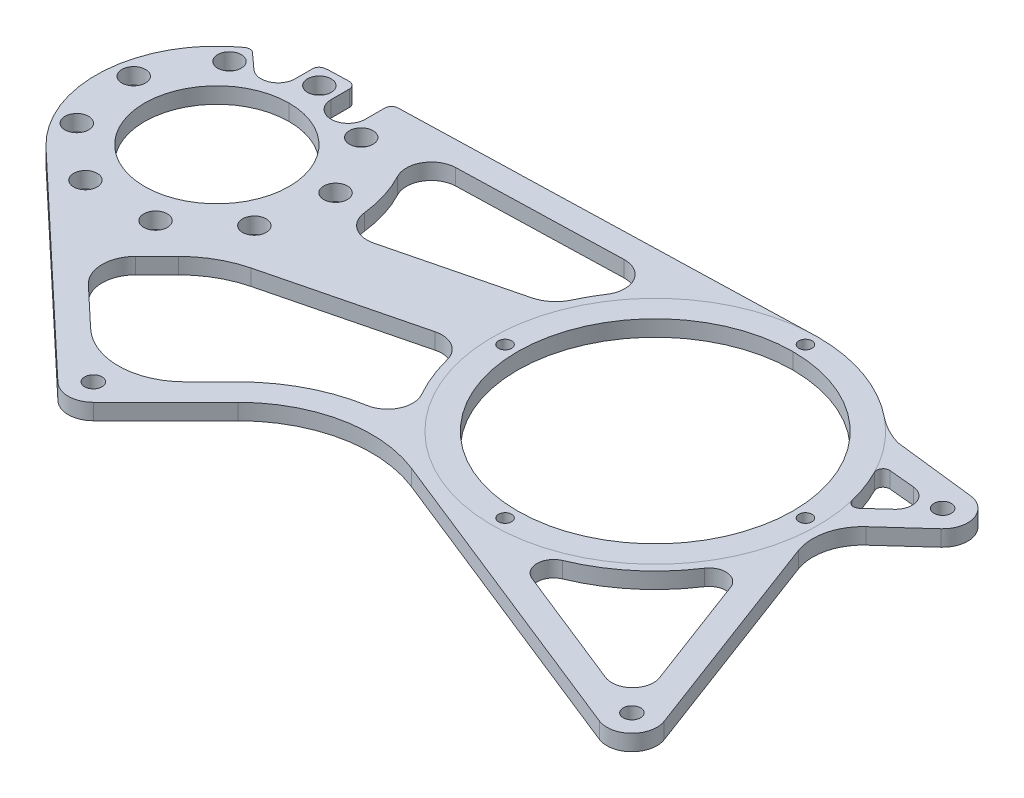
SolidWorks part; units mm, degrees
material "6061-T6 (SS)"
ref_plane "X-Y Datum" through (0, 0, 0) normal (0, 0, 1) x (1, 0, 0)
ref_plane "X-Z Datum" through (0, 0, 0) normal (0, 1, 0) x (1, 0, 0)
ref_plane "Y-Z Datum" through (0, 0, 0) normal (1, 0, 0) x (0, 0, -1)
sketch "Master Sketch " plane through (0, 0, 0) normal (0, 1, 0) x (1, 0, 0)
  line L0 (0, 0) -> (116.84, 0) construction
  line L1 (0, 0) -> (-54.61, 0) construction
  line L2 (116.84, 0) -> (228.6, 0) construction
  line L3 (228.6, 0) -> (228.6, 146.8882) construction
  line L4 (123.19, 0) -> (123.19, 116.0018) construction
  line L5 (-54.61, 0) -> (-414.02, 0) construction
  line L6 (-54.61, 0) -> (-54.61, 127) construction
  line L7 (123.19, 168.4528) -> (123.19, 177.9778) construction
  line L8 (228.6, 146.8882) -> (123.19, 116.0018) construction
  line L9 (123.19, 116.0018) -> (228.6, 0) construction
  line L10 (0, 0) -> (123.19, 116.0018) construction
  line L11 (0, 0) -> (-54.61, 127) construction
  line L12 (-54.61, 127) -> (123.19, 116.0018) construction
  line L13 (228.6, 146.8882) -> (-54.61, 127) construction
  line L14 (0, 0) -> (0, 123.622) construction
  line L15 (-86.1521, 93.553) -> (-6.535, 18.4704)
  line L16 (-54.61, 172.974) -> (123.19, 177.9778)
  line L17 (194.7449, 124.6975) -> (209.653, 138.231)
  line L19 (189.7169, 103.8914) -> (220.4344, 22.1488)
  line L20 (6.7352, 18.6648) -> (34.256, 46.1856)
  line L21 (207.987, 9.9519) -> (89.0101, 57.4446)
  line L22 (204.3537, 154.7444) -> (173.1, 158.388)
  circle A0 centre (0, 0) radius 12.7 construction
  circle A1 centre (228.6, 146.8882) radius 12.7 construction
  circle A2 centre (228.6, 0) radius 12.7 construction
  circle A3 centre (-414.02, 0) radius 12.7 construction
  circle A4 centre (123.19, 116.0018) radius 52.451
  circle A5 centre (123.19, 116.0018) radius 57.15 construction
  circle A6 centre (123.19, 116.0018) radius 61.976 construction
  circle A7 centre (-54.61, 127) radius 45.974
  circle A8 centre (-54.61, 127) radius 39 construction
  circle A9 centre (203.2507, 145.2835) radius 3 construction
  circle A10 centre (211.5182, 18.7982) radius 3 construction
  circle A11 centre (0, 25.4) radius 3 construction
  circle A12 centre (0, 25.4) radius 9.525
  circle A13 centre (211.5182, 18.7982) radius 9.525
  circle A14 centre (203.2507, 145.2835) radius 9.525
  arc A17 (56.2619, 120.1418) -> (168.2859, 66.3745) centre (123.19, 116.0018) ccw construction
  arc A18 (123.19, 177.9778) -> (162.2274, 164.1382) centre (123.19, 116.0018) cw
  circle A19 centre (123.19, 116.0018) radius 67.056 construction
  arc A20 (194.7449, 124.6975) -> (189.7169, 103.8914) centre (207.5493, 110.5926) ccw
  arc A21 (173.1, 158.388) -> (162.2274, 164.1382) centre (182.226, 188.7982) cw
  arc A22 (89.0101, 57.4446) -> (34.256, 46.1856) centre (70.177, 10.2646) ccw
  circle A23 centre (-54.61, 127) radius 25.908 construction
  circle A24 centre (-54.61, 127) radius 27.4955
  circle A25 centre (123.19, 173.1518) radius 2.5 construction
  circle A26 centre (-41.2712, 163.648) radius 6.5
  circle A27 centre (-67.9488, 163.648) radius 6.5
  point P9 (123.19, 0)
  point P23 (-54.61, 166)
  point P27 (-41.2712, 163.648)
  point P28 (-29.5413, 156.8757)
  point P29 (-20.835, 146.5)
  point P30 (-16.2025, 133.7723)
  point P31 (-16.2025, 120.2277)
  point P32 (-20.835, 107.5)
  point P33 (-29.5413, 97.1243)
  point P34 (-41.2712, 90.352)
  point P35 (-54.61, 88)
  point P36 (-67.9488, 90.352)
  point P37 (-79.6787, 97.1243)
  point P38 (-88.385, 107.5)
  point P39 (-93.0175, 120.2277)
  point P40 (-93.0175, 133.7723)
  point P41 (-88.385, 146.5)
  point P42 (-79.6787, 156.8757)
  point P43 (-67.9488, 163.648)
  point P44 (-54.61, 127)
  point P66 (190.246, 116.0018)
  point P74 (185.166, 116.0018)
  point P75 (0, 0)
  point P77 (163.0683, 163.4438)
  point P80 (74.3713, 70.0317)
  point P87 (0, 0)
  point P88 (0, 0)
  dimension "D1" = 105.41
  dimension "D2" = 25.4
  dimension "D8" = 116.0018
  dimension "D11" = 104.902
  dimension "D12" = 114.3
  dimension "D13" = 123.952
  dimension "D14" = 91.948
  dimension "D15" = 78
  dimension "D17" = 6
  dimension "D21" = 19.05
  dimension "D23" = 13
  dimension "D25" = 19.05
  dimension "D26" = 31.75
  dimension "D27" = 50.8
  dimension "D28" = 1.5875
  dimension "D30" = 51.816
  dimension "D31" = 5
  dimension "D32" = 25.4
  dimension "D3" = 146.8882
  dimension "D4" = 171.45
  dimension "D5" = 111.76
  dimension "D6" = 116.84
  dimension "D7" = 54.61
  dimension "D9" = 642.62
  dimension "D10" = 127
  dimension "D18" = 25.4
  dimension "D19" = 25.4
  dimension "D20" = 5.588
  dimension "D22" = 228.6
  dimension "D29" = 45
  dimension "D33" = 42.1263
  dimension "D34" = 13.1045
  dimension "D24" = 5.08
  dimension "D16" = 18
extrude "Boss-Extrude2" add sketch "Master Sketch " along normal mid plane 6.096
hole_wizard "Ø5.0mm Dowel Hole1" positions "Sketch26" profile "Sketch27" hole size "Ø5.0" standard "ANSI Metric" end condition through all
sketch "Sketch26" plane through (0, 3.048, 0) normal (0, 1, 0) x (1, 0, 0)
  point P5 (123.19, 173.1518)
sketch "Sketch27" plane through (123.19, 3.048, -173.1518) normal (1, 0, 0) x (0, 0, 1)
  line L0 (0, 0) -> (0, 6.096)
  line L1 (0, 6.096) -> (2.5, 6.096)
  line L2 (2.5, 6.096) -> (2.5, 0)
  line L5 (2.5, 0) -> (0, 0)
  line L11 (0, -6.35) -> (0, 107.95) construction
  dimension "Thru Hole Dia." = 5
  dimension "Thru Hole Depth" = 6.096
pattern_circular "CirPattern4" count 4 over 360 about axis through (123.19, 0, -116.0018) along (0, 1, 0) of "Ø5.0mm Dowel Hole1"
hole_wizard "M6 Clearance Hole4" positions "Sketch20" profile "Sketch21" hole size "M6" standard "ANSI Metric" end condition through all
sketch "Sketch20" plane through (0, 3.048, 0) normal (0, 1, 0) x (1, 0, 0)
  point P0 (203.2507, 145.2835)
  point P3 (211.5182, 18.7982)
  point P6 (0, 25.4)
  point P9 (203.2507, 145.2835)
sketch "Sketch21" plane through (203.2507, 3.048, -145.2835) normal (1, 0, 0) x (0, 0, 1)
  line L0 (0, 0) -> (0, 6.096)
  line L1 (0, 6.096) -> (3.3, 6.096)
  line L2 (3.3, 6.096) -> (3.3, 0)
  line L5 (3.3, 0) -> (0, 0)
  line L11 (0, -6.35) -> (0, 107.95) construction
  dimension "Thru Hole Dia." = 6.6
  dimension "Thru Hole Depth" = 6.096
hole_wizard "M8 Clearance Hole1" positions "Sketch24" profile "Sketch25" hole size "M8" standard "ANSI Metric" end condition through all
sketch "Sketch24" plane through (0, 3.048, 0) normal (0, 1, 0) x (1, 0, 0)
  point P2 (-54.61, 166)
sketch "Sketch25" plane through (-54.61, 3.048, -166) normal (1, 0, 0) x (0, 0, 1)
  line L0 (0, 0) -> (0, 6.096)
  line L1 (0, 6.096) -> (4.5, 6.096)
  line L2 (4.5, 6.096) -> (4.5, 0)
  line L5 (4.5, 0) -> (0, 0)
  line L11 (0, -6.35) -> (0, 107.95) construction
  dimension "Thru Hole Dia." = 9
  dimension "Thru Hole Depth" = 6.096
pattern_circular "CirPattern3" count 9 over 360 about axis through (-54.61, 0, -127) along (0, 1, 0) of "M8 Clearance Hole1"
ref_plane "Plane2" through (-54.61, 0, 0) normal (1, 0, 0) x (0, 0, -1)
ref_plane "Plane1" through (123.19, 0, 0) normal (1, 0, 0) x (0, 0, -1)
split line "Split Line2"
split line "Split Line3"
ref_point "Point2"
ref_point "Point3"
sketch "Sketch28" plane through (0, 3.048, 0) normal (0, 1, 0) x (1, 0, 0)
  circle A0 centre (123.19, 116.0018) radius 61.976 construction
  circle A1 centre (123.19, 116.0018) radius 61.976
split line "Split Line4"
sketch "Topology 1" plane through (0, 3.048, 0) normal (0, 1, 0) x (1, 0, 0)
  line L0 (145.3498, 45.211) -> (198.1607, 24.1302)
  line L1 (206.4589, 32.2614) -> (188.0555, 81.2349)
  line L2 (195.7351, 153.1787) -> (183.0397, 153.6291)
  line L3 (92.5413, 66.2908) -> (211.5182, 18.7982) construction
  line L4 (211.5182, 18.7982) -> (180.8006, 100.5409) construction
  line L5 (191.1278, 134.2783) -> (199.7781, 142.1311)
  line L6 (188.3427, 131.75) -> (203.2507, 145.2835) construction
  line L7 (204.3537, 154.7444) -> (173.1, 158.388)
  line L8 (6.7352, 18.6648) -> (34.256, 46.1856) construction
  line L9 (119.7044, 177.8797) -> (123.19, 177.9778) construction
  line L10 (119.7044, 177.8797) -> (123.19, 177.9778)
  line L11 (6.7352, 18.6648) -> (34.256, 46.1856)
  line L12 (11.5992, 36.9992) -> (27.5208, 52.9208)
  line L14 (-17.1171, 47.0221) -> (-17.1171, 64.5798)
  line L15 (-6.2723, 77.1436) -> (59.6042, 86.8711)
  line L16 (119.7044, 177.8797) -> (-54.61, 172.974)
  line L17 (-86.1521, 93.553) -> (-6.535, 18.4704)
  line L18 (6.7352, 18.6648) -> (34.256, 46.1856)
  line L19 (89.0101, 57.4446) -> (207.987, 9.9519)
  line L20 (220.4344, 22.1488) -> (189.7169, 103.8914)
  line L21 (194.7449, 124.6975) -> (209.653, 138.231)
  line L22 (204.3537, 154.7444) -> (173.1, 158.388)
  line L23 (119.7044, 177.8797) -> (-54.61, 172.974)
  line L24 (-86.1521, 93.553) -> (-6.535, 18.4704)
  line L26 (89.0101, 57.4446) -> (207.987, 9.9519)
  line L27 (220.4344, 22.1488) -> (189.7169, 103.8914)
  line L28 (194.7449, 124.6975) -> (209.653, 138.231)
  line L30 (73.4651, 167.0496) -> (-14.7002, 164.5684)
  line L31 (-4.4748, 145.7986) -> (62.0635, 147.6712)
  line L32 (-13.1304, 37.7826) -> (-11.934, 36.6543)
  line L33 (119.9724, 168.3585) -> (-54.342, 163.4528) construction
  line L34 (0, 25.4) -> (27.5208, 52.9208) construction
  arc A0 (162.2274, 164.1382) -> (123.19, 177.9778) centre (123.19, 116.0018) ccw construction
  arc A1 (162.2274, 164.1382) -> (123.19, 177.9778) centre (123.19, 116.0018) ccw
  arc A2 (145.5002, 54.1144) -> (179.5195, 82.0197) centre (123.19, 116.0018) ccw
  arc A3 (179.5195, 82.0197) -> (188.0555, 81.2349) centre (183.5974, 79.5596) cw
  arc A4 (119.4901, 181.6837) -> (164.6272, 167.0974) centre (123.19, 116.0018) ccw construction
  arc A5 (145.5002, 54.1144) -> (145.3498, 45.211) centre (147.1154, 49.6341) ccw
  arc A6 (206.4589, 32.2614) -> (198.1607, 24.1302) centre (200.5148, 30.0277) cw
  arc A7 (172.1385, 154.0158) -> (184.0265, 127.8317) centre (123.19, 116.0018) cw
  arc A8 (162.2274, 164.1382) -> (173.1, 158.388) centre (182.226, 188.7982) ccw
  arc A9 (119.7044, 177.8797) -> (162.2274, 164.1382) centre (123.19, 116.0018) ccw
  arc A10 (-54.61, 172.974) -> (-86.1521, 93.553) centre (-54.61, 127) ccw
  arc A11 (-6.535, 18.4704) -> (6.7352, 18.6648) centre (0, 25.4) ccw
  arc A12 (89.0101, 57.4446) -> (34.256, 46.1856) centre (70.177, 10.2646) ccw
  arc A13 (207.987, 9.9519) -> (220.4344, 22.1488) centre (211.5182, 18.7982) ccw
  arc A14 (194.7449, 124.6975) -> (189.7169, 103.8914) centre (207.5493, 110.5926) ccw
  arc A15 (209.653, 138.231) -> (204.3537, 154.7444) centre (203.2507, 145.2835) ccw
  arc A16 (162.2274, 164.1382) -> (173.1, 158.388) centre (182.226, 188.7982) ccw
  arc A17 (119.7044, 177.8797) -> (162.2274, 164.1382) centre (123.19, 116.0018) ccw
  arc A18 (-54.61, 172.974) -> (-86.1521, 93.553) centre (-54.61, 127) ccw
  arc A19 (-6.535, 18.4704) -> (6.7352, 18.6648) centre (0, 25.4) ccw
  arc A21 (207.987, 9.9519) -> (220.4344, 22.1488) centre (211.5182, 18.7982) ccw
  arc A22 (194.7449, 124.6975) -> (189.7169, 103.8914) centre (207.5493, 110.5926) ccw
  arc A23 (209.653, 138.231) -> (204.3537, 154.7444) centre (203.2507, 145.2835) ccw
  arc A24 (180.1768, 148.8698) -> (185.9641, 135.6794) centre (123.19, 116.0018) cw
  arc A25 (175.1477, 156.3527) -> (187.7664, 128.559) centre (123.19, 116.0018) cw construction
  arc A26 (191.1278, 134.2783) -> (185.9641, 135.6794) centre (188.9937, 136.6291) cw
  arc A27 (183.0397, 153.6291) -> (180.1768, 148.8698) centre (182.9271, 150.4561) ccw
  arc A28 (199.7781, 142.1311) -> (195.7351, 153.1787) centre (195.51, 146.8327) ccw
  arc A29 (89.0101, 57.4446) -> (34.256, 46.1856) centre (70.177, 10.2646) ccw construction
  arc A30 (89.0101, 57.4446) -> (34.256, 46.1856) centre (70.177, 10.2646) ccw
  arc A31 (63.8869, 70.2607) -> (27.5208, 52.9208) centre (70.177, 10.2646) ccw
  arc A32 (7.5766, 36.6135) -> (-7.9019, 36.3867) centre (0, 25.4) ccw
  arc A33 (67.8443, 88.1113) -> (82.4046, 69.3373) centre (123.19, 116.0018) ccw
  arc A34 (65.8116, 83.8223) -> (68.3344, 79.6884) centre (123.19, 116.0018) ccw
  arc A35 (64.4419, 86.3967) -> (79.8973, 66.4686) centre (123.19, 116.0018) ccw construction
  arc A36 (-10.3254, 149.2911) -> (-17.0182, 159.3246) centre (-54.61, 127) ccw
  arc A37 (70.0507, 147.896) -> (88.6754, 167.4777) centre (123.19, 116.0018) cw
  arc A38 (67.2815, 150.6721) -> (75.8397, 161.6717) centre (123.19, 116.0018) cw
  arc A39 (66.7839, 149.8567) -> (86.5536, 170.6422) centre (123.19, 116.0018) cw construction
  arc A40 (-17.0182, 159.3246) -> (-14.7002, 164.5684) centre (-14.6109, 161.3947) cw
  arc A41 (92.5413, 66.2908) -> (27.5208, 52.9208) centre (70.177, 10.2646) ccw construction
  arc A42 (-10.3254, 149.2911) -> (-4.4748, 145.7986) centre (-4.6534, 152.1461) ccw
  arc A43 (67.2815, 150.6721) -> (62.0635, 147.6712) centre (61.8849, 154.0187) cw
  arc A44 (75.8397, 161.6717) -> (73.4651, 167.0496) centre (73.5544, 163.8759) ccw
  arc A45 (-6.2723, 77.1436) -> (-17.1171, 64.5798) centre (-4.4171, 64.5798) ccw
  arc A46 (-17.1171, 47.0221) -> (-13.1304, 37.7826) centre (-4.4171, 47.0221) ccw
  arc A47 (7.5766, 36.6135) -> (11.5992, 36.9992) centre (9.3541, 39.2442) ccw
  arc A48 (-7.9019, 36.3867) -> (-11.934, 36.6543) centre (-9.7557, 38.9642) cw
  arc A49 (65.8116, 83.8223) -> (59.6042, 86.8711) centre (60.4947, 80.8405) ccw
  arc A50 (68.3344, 79.6884) -> (63.8869, 70.2607) centre (63.2512, 76.3235) cw
  point P69 (-79.6171, 100.4826)
  point P105 (-17.1171, 75.5422)
  point P108 (-17.1171, 41.5422)
  dimension "D4" = 4.7625
  dimension "D5" = 6.35
  dimension "D8" = 3.175
  dimension "D9" = 6.35
  dimension "D11" = 3.175
  dimension "D17" = 6.35
  dimension "D18" = 6.35
  dimension "D19" = 3.175
  dimension "D20" = 12.7
  dimension "D21" = 12.7
  dimension "D22" = 3.175
  dimension "D23" = 6.096
  dimension "D24" = 49.5784
  dimension "D25" = 13.5331
  dimension "D14" = 19.05
  dimension "D15" = 34
  dimension "D1" = 0
  dimension "D2" = 9.525
  dimension "D3" = 3.81
  dimension "D6" = 9.525
  dimension "D7" = 3.81
  dimension "D10" = 9.525
  dimension "D12" = 3.81
  dimension "D13" = 9.525
  dimension "D16" = 3.81
sketch "Topology 3" plane through (0, 3.048, 0) normal (0, 1, 0) x (1, 0, 0)
  line L0 (148.2326, 44.0603) -> (194.8213, 25.4632)
  line L1 (205.1941, 35.6272) -> (188.9001, 78.9873)
  line L2 (190.6747, 146.7902) -> (180.8059, 147.7126)
  line L3 (187.4193, 129.4727) -> (194.3519, 135.7661)
  line L4 (189.0588, 130.9611) -> (203.9669, 144.4946) construction
  line L5 (17.4418, 42.8418) -> (27.5208, 52.9208)
  line L6 (-33.0328, 56.5514) -> (-17.9453, 42.3233)
  line L7 (119.7044, 177.8797) -> (-54.61, 172.974)
  line L8 (-86.1521, 93.553) -> (-6.535, 18.4704)
  line L9 (6.7352, 18.6648) -> (34.256, 46.1856)
  line L10 (89.0101, 57.4446) -> (207.987, 9.9519)
  line L11 (220.4344, 22.1488) -> (189.7169, 103.8914)
  line L12 (194.7449, 124.6975) -> (209.653, 138.231)
  line L13 (204.3537, 154.7444) -> (173.1, 158.388)
  line L14 (119.7044, 177.8797) -> (-54.61, 172.974)
  line L15 (-86.1521, 93.553) -> (-6.535, 18.4704)
  line L16 (6.7352, 18.6648) -> (34.256, 46.1856)
  line L17 (89.0101, 57.4446) -> (207.987, 9.9519)
  line L18 (220.4344, 22.1488) -> (189.7169, 103.8914)
  line L19 (194.7449, 124.6975) -> (209.653, 138.231)
  line L22 (-7.4578, 92.9346) -> (48.4864, 106.9206)
  line L23 (60.6168, 166.688) -> (-1.6638, 164.9353)
  line L24 (7.6514, 124.4645) -> (55.6594, 136.4665)
  line L25 (-33.2997, 74.7712) -> (-25.158, 82.9129)
  line L26 (119.9724, 168.3585) -> (-54.342, 163.4528) construction
  line L27 (-79.6171, 100.4826) -> (0, 25.4) construction
  line L28 (0, 25.4) -> (27.5208, 52.9208) construction
  line L29 (92.5413, 66.2908) -> (211.5182, 18.7982) construction
  line L30 (211.5182, 18.7982) -> (180.8006, 100.5409) construction
  line L32 (204.3537, 154.7444) -> (173.1, 158.388)
  line L33 (203.2507, 145.2835) -> (123.19, 116.0018) construction
  arc A0 (123.19, 54.0258) -> (182.1581, 96.9285) centre (123.19, 116.0018) ccw
  arc A1 (148.1536, 55.8231) -> (177.6482, 80.2392) centre (123.19, 116.0018) ccw
  arc A3 (178.398, 144.1638) -> (183.3968, 130.7042) centre (123.19, 116.0018) cw
  arc A4 (59.8962, 69.7071) -> (27.5208, 52.9208) centre (70.177, 10.2646) ccw
  arc A7 (61.4889, 110.1712) -> (82.4046, 69.3373) centre (123.19, 116.0018) ccw
  arc A8 (162.2274, 164.1382) -> (173.1, 158.388) centre (182.226, 188.7982) ccw
  arc A9 (119.7044, 177.8797) -> (162.2274, 164.1382) centre (123.19, 116.0018) ccw
  arc A10 (-54.61, 172.974) -> (-86.1521, 93.553) centre (-54.61, 127) ccw
  arc A11 (-6.535, 18.4704) -> (6.7352, 18.6648) centre (0, 25.4) ccw
  arc A12 (89.0101, 57.4446) -> (34.256, 46.1856) centre (70.177, 10.2646) ccw
  arc A13 (207.987, 9.9519) -> (220.4344, 22.1488) centre (211.5182, 18.7982) ccw
  arc A14 (194.7449, 124.6975) -> (189.7169, 103.8914) centre (207.5493, 110.5926) ccw
  arc A15 (209.653, 138.231) -> (204.3537, 154.7444) centre (203.2507, 145.2835) ccw
  arc A16 (162.2274, 164.1382) -> (173.1, 158.388) centre (182.226, 188.7982) ccw
  arc A17 (119.7044, 177.8797) -> (162.2274, 164.1382) centre (123.19, 116.0018) ccw
  arc A18 (-54.61, 172.974) -> (-86.1521, 93.553) centre (-54.61, 127) ccw
  arc A19 (-6.535, 18.4704) -> (6.7352, 18.6648) centre (0, 25.4) ccw
  arc A20 (89.0101, 57.4446) -> (34.256, 46.1856) centre (70.177, 10.2646) ccw
  arc A21 (207.987, 9.9519) -> (220.4344, 22.1488) centre (211.5182, 18.7982) ccw
  arc A22 (194.7449, 124.6975) -> (189.7169, 103.8914) centre (207.5493, 110.5926) ccw
  arc A23 (209.653, 138.231) -> (204.3537, 154.7444) centre (203.2507, 145.2835) ccw
  arc A24 (60.0304, 100.017) -> (66.5532, 83.8005) centre (123.19, 116.0018) ccw
  arc A25 (63.439, 132.459) -> (88.6754, 167.4777) centre (123.19, 116.0018) cw
  arc A26 (64.0981, 143.4389) -> (68.8318, 151.9162) centre (123.19, 116.0018) cw
  arc A27 (-4.1248, 132.6464) -> (-9.7981, 150.9276) centre (-54.61, 127) ccw
  arc A28 (92.5413, 66.2908) -> (27.5208, 52.9208) centre (70.177, 10.2646) ccw construction
  arc A29 (58.328, 109.8725) -> (80.3152, 66.9467) centre (123.19, 116.0018) ccw construction
  arc A30 (60.378, 133.3021) -> (86.9072, 170.1148) centre (123.19, 116.0018) cw construction
  arc A31 (123.19, 50.8508) -> (185.179, 95.9514) centre (123.19, 116.0018) ccw construction
  arc A33 (205.1941, 35.6272) -> (194.8213, 25.4632) centre (197.7639, 32.8351) cw
  arc A34 (188.9001, 78.9873) -> (177.6482, 80.2392) centre (182.956, 76.7536) ccw
  arc A35 (148.1536, 55.8231) -> (148.2326, 44.0603) centre (150.5867, 49.9578) ccw
  arc A36 (183.3968, 130.7042) -> (187.4193, 129.4727) centre (185.7743, 131.2848) ccw
  arc A37 (180.8059, 147.7126) -> (178.398, 144.1638) centre (180.5781, 145.2759) ccw
  arc A38 (194.3519, 135.7661) -> (190.6747, 146.7902) centre (190.0837, 140.4678) ccw
  arc A42 (48.4864, 106.9206) -> (60.0304, 100.017) centre (50.7965, 97.68) cw
  arc A43 (59.8962, 69.7071) -> (66.5532, 83.8005) centre (58.2729, 79.0927) ccw
  arc A46 (-1.6638, 164.9353) -> (-9.7981, 150.9276) centre (-1.3958, 155.4141) ccw
  arc A47 (7.6514, 124.4645) -> (-4.1248, 132.6464) centre (5.3412, 133.7051) cw
  arc A48 (55.6594, 136.4665) -> (64.0981, 143.4389) centre (52.5792, 148.7873) ccw
  arc A49 (68.8318, 151.9162) -> (60.6168, 166.688) centre (60.8847, 157.1668) ccw
  arc A50 (-33.2997, 74.7712) -> (-33.0328, 56.5514) centre (-24.3195, 65.7909) ccw
  arc A51 (-6.535, 18.4704) -> (6.7352, 18.6648) centre (0, 25.4) ccw
  arc A55 (-7.4578, 92.9346) -> (-25.158, 82.9129) centre (1.7828, 55.9721) ccw
  arc A59 (17.4418, 42.8418) -> (-17.9453, 42.3233) centre (-0.5187, 60.8023) cw
  point P31 (205.5752, 154.3754)
  point P33 (169.7015, 153.9896)
  point P38 (177.1898, 152.4528)
  point P40 (180.3051, 146.2445)
  point P43 (186.8894, 129.6779)
  point P97 (6.7352, 32.1352)
  dimension "D11" = 7.9375
  dimension "D12" = 6.35
  dimension "D13" = 12.7
  dimension "D14" = 6.35
  dimension "D15" = 25.4
  dimension "D16" = 38.1
  dimension "D17" = 9.525
  dimension "D18" = 2.4474
  dimension "D21" = 9.525
  dimension "D22" = 9.525
  dimension "D23" = 12.7
  dimension "D24" = 9.525
  dimension "D25" = 50.8
  dimension "D20" = 26.924
  dimension "D26" = 52
  dimension "D4" = 14.02
  dimension "D5" = 22.6726
  dimension "D1" = 0
  dimension "D2" = 9.525
  dimension "D3" = 3.175
  dimension "D6" = 9.525
  dimension "D7" = 9.525
  dimension "D8" = 3.175
  dimension "D9" = 9.525
  dimension "D10" = 3.175
extrude "Cut-Extrude1" [suppressed] cut sketch "Topology 1" against normal through all contours A38 A44 L30 A40 A36 A42 L31 A43 | A50 A34 A49 L15 A45 L14 A46 L32 A48 A32 A47 L12 A31 | A6 L1 A3 A2 A5 L0 | L5 A28 L2 A27 A24 A26
extrude "Cut-Extrude2" cut sketch "Topology 3" against normal through all
sketch "Sketch29" plane through (0, -3.048, 0) normal (0, -1, 0) x (1, 0, 0)
  line L0 (-72.3056, -158.8243) -> (-79.7134, -165.5153)
  line L1 (-61.4488, -163.648) -> (-61.4488, -172.4625)
  line L2 (-47.7712, -163.648) -> (-47.7712, -173.1665)
  line L3 (-34.7712, -163.648) -> (-34.7712, -173.5323)
  line L4 (-54.61, -172.974) -> (123.19, -177.9778) construction
  line L5 (-47.7712, -173.1665) -> (-34.7712, -173.5323)
  circle A1 centre (-41.2712, -163.648) radius 6.5 construction
  circle A2 centre (-67.9488, -163.648) radius 6.5 construction
  circle A3 centre (-41.2712, -163.648) radius 6.5 construction
  circle A4 centre (-67.9488, -163.648) radius 6.5 construction
  arc A5 (-86.1521, -93.553) -> (-54.61, -172.974) centre (-54.61, -127) ccw construction
  arc A6 (-86.1521, -93.553) -> (-54.61, -172.974) centre (-54.61, -127) ccw construction
  arc A7 (-72.3056, -158.8243) -> (-61.4488, -163.648) centre (-67.9488, -163.648) ccw
  arc A8 (-61.4488, -172.4625) -> (-79.7134, -165.5153) centre (-54.61, -127) cw
  arc A9 (-47.7712, -163.648) -> (-34.7712, -163.648) centre (-41.2712, -163.648) ccw
  dimension "D1" = 7.4078
extrude "Cut-Extrude3" cut sketch "Sketch29" against normal through all
fillet "Fillet1" radius 2.54 4 edges at (-79.7134, 0, -165.5153) (-61.4488, 0, -172.4625) (-47.7712, 0, -173.1665) (-34.7712, 0, -173.5323)
